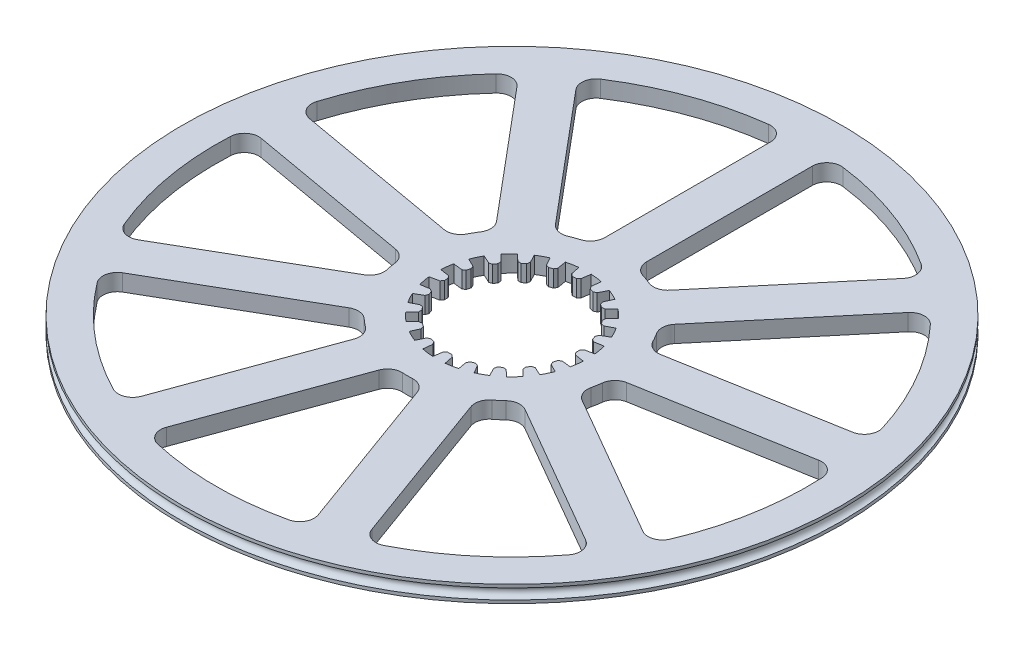
SolidWorks part; units mm, degrees
ref_plane "Front Plane" through (0, 0, 0) normal (0, 0, 1) x (1, 0, 0)
ref_plane "Top Plane" through (0, 0, 0) normal (0, 1, 0) x (1, 0, 0)
ref_plane "Right Plane" through (0, 0, 0) normal (1, 0, 0) x (0, 0, -1)
sketch "Sketch1" plane through (0, 0, 0) normal (0, 1, 0) x (1, 0, 0)
  circle A0 centre (0, 0) radius 2000.25
  dimension "D1" = 4000.5
extrude "Boss-Extrude1" add sketch "Sketch1" along normal blind 101.6
sketch "Sketch2" plane through (0, 101.6, 0) normal (0, 1, 0) x (1, 0, 0)
  circle A0 centre (0, 0) radius 457.2
  dimension "D1" = 914.4
extrude "Cut-Extrude1" cut sketch "Sketch2" against normal through all
sketch "Sketch3" plane through (0, 101.6, 0) normal (0, 1, 0) x (1, 0, 0)
  line L0 (-127, 1695.9045) -> (-127, 690.0124)
  line L1 (127, 690.0124) -> (127, 1695.9045)
  line L2 (992.8188, 1380.7723) -> (346.2438, 610.2142)
  line L3 (540.8191, 446.9462) -> (1187.3941, 1217.5042)
  line L4 (1648.0866, 419.5613) -> (657.4763, 244.89)
  line L5 (701.5829, -5.2512) -> (1692.1932, 169.4201)
  line L6 (1532.1964, -737.967) -> (661.0683, -235.021)
  line L7 (534.0683, -454.9914) -> (1405.1964, -957.9375)
  line L8 (699.3745, -1550.1924) -> (355.3391, -604.963)
  line L9 (116.6572, -691.8361) -> (460.6925, -1637.0655)
  line L10 (-460.6925, -1637.0655) -> (-116.6572, -691.8361)
  line L11 (-355.3391, -604.963) -> (-699.3745, -1550.1924)
  line L12 (-1405.1964, -957.9375) -> (-534.0683, -454.9914)
  line L13 (-661.0683, -235.021) -> (-1532.1964, -737.967)
  line L14 (-1692.1932, 169.4201) -> (-701.5829, -5.2512)
  line L15 (-657.4763, 244.89) -> (-1648.0866, 419.5613)
  line L16 (-1187.3941, 1217.5042) -> (-540.8191, 446.9462)
  line L17 (-346.2438, 610.2142) -> (-992.8188, 1380.7723)
  arc A0 (-629.8844, -80.4399) -> (-619.4098, -139.8443) centre (0, 0) ccw
  arc A1 (-1318.8161, 1220.7017) -> (-1716.5668, 531.7774) centre (0, 0) ccw
  circle A2 centre (0, 0) radius 2000.25 construction
  arc A3 (-225.6198, 1782.8304) -> (-973.1465, 1510.753) centre (0, 0) ccw
  arc A4 (973.1465, 1510.753) -> (225.6198, 1782.8304) centre (0, 0) ccw
  arc A5 (-1794.9237, 87.3931) -> (-1656.7864, -696.0227) centre (0, 0) ccw
  arc A6 (-430.8137, -466.5025) -> (-384.6053, -505.276) centre (0, 0) ccw
  arc A7 (-1431.1665, -1086.8077) -> (-821.7772, -1598.1461) centre (0, 0) ccw
  arc A8 (-397.7506, -1752.4791) -> (397.7506, -1752.4791) centre (0, 0) ccw
  arc A9 (-30.1604, -634.2833) -> (30.1604, -634.2833) centre (0, 0) ccw
  arc A10 (384.6053, -505.276) -> (430.8137, -466.5025) centre (0, 0) ccw
  arc A11 (821.7772, -1598.1461) -> (1431.1665, -1086.8077) centre (0, 0) ccw
  arc A12 (1656.7864, -696.0227) -> (1794.9237, 87.3931) centre (0, 0) ccw
  arc A13 (619.4098, -139.8443) -> (629.8844, -80.4399) centre (0, 0) ccw
  arc A14 (564.3857, 291.022) -> (534.2253, 343.2613) centre (0, 0) ccw
  arc A15 (1716.5668, 531.7774) -> (1318.8161, 1220.7017) centre (0, 0) ccw
  arc A16 (245.2792, 585.7159) -> (188.5962, 606.3468) centre (0, 0) ccw
  arc A17 (-188.5962, 606.3468) -> (-245.2792, 585.7159) centre (0, 0) ccw
  arc A18 (-534.2253, 343.2613) -> (-564.3857, 291.022) centre (0, 0) ccw
  arc A19 (-1648.0866, 419.5613) -> (-1716.5668, 531.7774) centre (-1632.8717, 505.8494) cw
  arc A20 (-1187.3941, 1217.5042) -> (-1318.8161, 1220.7017) centre (-1254.5143, 1161.1836) ccw
  arc A21 (-992.8188, 1380.7723) -> (-973.1465, 1510.753) centre (-925.6985, 1437.0928) cw
  arc A22 (-127, 1695.9045) -> (-225.6198, 1782.8304) centre (-214.6192, 1695.9045) ccw
  arc A23 (127, 1695.9045) -> (225.6198, 1782.8304) centre (214.6192, 1695.9045) cw
  arc A24 (992.8188, 1380.7723) -> (973.1465, 1510.753) centre (925.6985, 1437.0928) ccw
  arc A25 (1187.3941, 1217.5042) -> (1318.8161, 1220.7017) centre (1254.5143, 1161.1836) cw
  arc A26 (1648.0866, 419.5613) -> (1716.5668, 531.7774) centre (1632.8717, 505.8494) ccw
  arc A27 (1692.1932, 169.4201) -> (1794.9237, 87.3931) centre (1707.4082, 83.132) cw
  arc A28 (1532.1964, -737.967) -> (1656.7864, -696.0227) centre (1576.006, -662.0865) ccw
  arc A29 (1405.1964, -957.9375) -> (1431.1665, -1086.8077) centre (1361.3868, -1033.818) cw
  arc A30 (699.3745, -1550.1924) -> (821.7772, -1598.1461) centre (781.7096, -1520.2249) ccw
  arc A31 (460.6925, -1637.0655) -> (397.7506, -1752.4791) centre (378.3574, -1667.0331) cw
  arc A32 (-460.6925, -1637.0655) -> (-397.7506, -1752.4791) centre (-378.3574, -1667.0331) ccw
  arc A33 (-699.3745, -1550.1924) -> (-821.7772, -1598.1461) centre (-781.7096, -1520.2249) cw
  arc A34 (-1405.1964, -957.9375) -> (-1431.1665, -1086.8077) centre (-1361.3868, -1033.818) ccw
  arc A35 (-534.0683, -454.9914) -> (-430.8137, -466.5025) centre (-490.2587, -530.8719) cw
  arc A36 (-355.3391, -604.963) -> (-384.6053, -505.276) centre (-437.6743, -574.9955) ccw
  arc A37 (-116.6572, -691.8361) -> (-30.1604, -634.2833) centre (-34.322, -721.8037) cw
  arc A38 (116.6572, -691.8361) -> (30.1604, -634.2833) centre (34.322, -721.8037) ccw
  arc A39 (355.3391, -604.963) -> (384.6053, -505.276) centre (437.6743, -574.9955) cw
  arc A40 (534.0683, -454.9914) -> (430.8137, -466.5025) centre (490.2587, -530.8719) ccw
  arc A41 (661.0683, -235.021) -> (619.4098, -139.8443) centre (704.8779, -159.1405) cw
  arc A42 (701.5829, -5.2512) -> (629.8844, -80.4399) centre (716.7978, -91.5393) ccw
  arc A43 (657.4763, 244.89) -> (564.3857, 291.022) centre (642.2613, 331.1781) cw
  arc A44 (540.8191, 446.9462) -> (534.2253, 343.2613) centre (607.9393, 390.6256) ccw
  arc A45 (346.2438, 610.2142) -> (245.2792, 585.7159) centre (279.1236, 666.5348) cw
  arc A46 (127, 690.0124) -> (188.5962, 606.3468) centre (214.6192, 690.0124) ccw
  arc A47 (-127, 690.0124) -> (-188.5962, 606.3468) centre (-214.6192, 690.0124) cw
  arc A48 (-346.2438, 610.2142) -> (-245.2792, 585.7159) centre (-279.1236, 666.5348) ccw
  arc A49 (-540.8191, 446.9462) -> (-534.2253, 343.2613) centre (-607.9393, 390.6256) cw
  arc A50 (-657.4763, 244.89) -> (-564.3857, 291.022) centre (-642.2613, 331.1781) ccw
  arc A51 (-701.5829, -5.2512) -> (-629.8844, -80.4399) centre (-716.7978, -91.5393) cw
  arc A52 (-661.0683, -235.021) -> (-619.4098, -139.8443) centre (-704.8779, -159.1405) ccw
  arc A53 (-1532.1964, -737.967) -> (-1656.7864, -696.0227) centre (-1576.006, -662.0865) cw
  arc A54 (-1692.1932, 169.4201) -> (-1794.9237, 87.3931) centre (-1707.4082, 83.132) ccw
  point P44 (0, 0)
  point P49 (-127, 1792.5568)
  point P98 (127, 622.1704)
  point P101 (-127, 622.1704)
  dimension "D1" = 1270
  dimension "D3" = 203.2
  dimension "D5" = 87.6192
  dimension "D2" = 254
  dimension "D4" = 9
extrude "Cut-Extrude2" cut sketch "Sketch3" against normal through all
sketch "Sketch4" plane through (0, 0, 0) normal (0, 0, 1) x (1, 0, 0)
  line L0 (2000.25, 0) -> (2000.25, 101.6) construction
  circle A0 centre (2000.25, 50.8) radius 31.75
  dimension "D1" = 63.5
ref_plane "Plane1" through (0, 50.8, 0) normal (0, 1, 0) x (1, 0, 0)
sketch "Sketch6" plane through (0, 50.8, 0) normal (0, 1, 0) x (1, 0, 0)
  circle A0 centre (0, 0) radius 1714.5
  dimension "D1" = 3429
sweep "Cut-Sweep1" cut profiles "Sketch4" path "Sketch6"
sketch "Sketch7" plane through (0, 101.6, 0) normal (0, 1, 0) x (1, 0, 0)
  line L0 (-48.8401, 454.5839) -> (-37.7961, 400.4709)
  line L1 (24.421, 456.5473) -> (16.2913, 401.9205)
  line L2 (-22.561, 388.3677) -> (1.7264, 389.0186)
  line L3 (-37.7961, 400.4709) -> (-22.561, 388.3677)
  line L4 (16.2913, 401.9205) -> (1.7264, 389.0186)
  line L5 (94.0245, 447.4274) -> (87.8061, 392.5501)
  line L6 (164.3067, 426.6558) -> (139.6942, 377.2148)
  line L7 (139.6942, 377.2148) -> (121.8553, 369.4452)
  line L8 (98.5554, 376.3313) -> (121.8553, 369.4452)
  line L9 (87.8061, 392.5501) -> (98.5554, 376.3313)
  line L10 (227.6852, 396.4736) -> (204.8132, 346.2037)
  line L11 (288.1088, 355.0002) -> (249.4229, 315.5847)
  line L12 (249.4229, 315.5847) -> (230.0561, 313.7079)
  line L13 (210.0246, 327.4571) -> (230.0561, 313.7079)
  line L14 (204.8132, 346.2037) -> (210.0246, 327.4571)
  line L15 (339.0586, 306.7102) -> (301.7718, 265.9685)
  line L16 (383.7089, 248.5947) -> (334.7363, 223.063)
  line L17 (334.7363, 223.063) -> (315.7374, 227.2627)
  line L18 (300.935, 246.529) -> (315.7374, 227.2627)
  line L19 (301.7718, 265.9685) -> (300.935, 246.529)
  line L20 (417.2425, 186.9238) -> (369.1908, 159.6985)
  line L21 (441.7488, 117.8551) -> (387.2834, 108.7063)
  line L22 (387.2834, 108.7063) -> (370.5122, 118.5714)
  line L23 (362.3879, 141.469) -> (370.5122, 118.5714)
  line L24 (369.1908, 159.6985) -> (362.3879, 141.469)
  line L25 (454.5839, 48.8401) -> (400.4709, 37.7961)
  line L26 (456.5473, -24.421) -> (401.9205, -16.2913)
  line L27 (401.9205, -16.2913) -> (389.0186, -1.7264)
  line L28 (388.3677, 22.561) -> (389.0186, -1.7264)
  line L29 (400.4709, 37.7961) -> (388.3677, 22.561)
  line L30 (447.4274, -94.0245) -> (392.5501, -87.8061)
  line L31 (426.6558, -164.3067) -> (377.2148, -139.6942)
  line L32 (377.2148, -139.6942) -> (369.4452, -121.8553)
  line L33 (376.3313, -98.5554) -> (369.4452, -121.8553)
  line L34 (392.5501, -87.8061) -> (376.3313, -98.5554)
  line L35 (396.4736, -227.6852) -> (346.2037, -204.8132)
  line L36 (355.0002, -288.1088) -> (315.5847, -249.4229)
  line L37 (315.5847, -249.4229) -> (313.7079, -230.0561)
  line L38 (327.4571, -210.0246) -> (313.7079, -230.0561)
  line L39 (346.2037, -204.8132) -> (327.4571, -210.0246)
  line L40 (306.7102, -339.0586) -> (265.9685, -301.7718)
  line L41 (248.5947, -383.7089) -> (223.063, -334.7363)
  line L42 (223.063, -334.7363) -> (227.2627, -315.7374)
  line L43 (246.529, -300.935) -> (227.2627, -315.7374)
  line L44 (265.9685, -301.7718) -> (246.529, -300.935)
  line L45 (186.9238, -417.2425) -> (159.6985, -369.1908)
  line L46 (117.8551, -441.7488) -> (108.7063, -387.2834)
  line L47 (108.7063, -387.2834) -> (118.5714, -370.5122)
  line L48 (141.469, -362.3879) -> (118.5714, -370.5122)
  line L49 (159.6985, -369.1908) -> (141.469, -362.3879)
  line L50 (48.8401, -454.5839) -> (37.7961, -400.4709)
  line L51 (-24.421, -456.5473) -> (-16.2913, -401.9205)
  line L52 (-16.2913, -401.9205) -> (-1.7264, -389.0186)
  line L53 (22.561, -388.3677) -> (-1.7264, -389.0186)
  line L54 (37.7961, -400.4709) -> (22.561, -388.3677)
  line L55 (-94.0245, -447.4274) -> (-87.8061, -392.5501)
  line L56 (-164.3067, -426.6558) -> (-139.6942, -377.2148)
  line L57 (-139.6942, -377.2148) -> (-121.8553, -369.4452)
  line L58 (-98.5554, -376.3313) -> (-121.8553, -369.4452)
  line L59 (-87.8061, -392.5501) -> (-98.5554, -376.3313)
  line L60 (-227.6852, -396.4736) -> (-204.8132, -346.2037)
  line L61 (-288.1088, -355.0002) -> (-249.4229, -315.5847)
  line L62 (-249.4229, -315.5847) -> (-230.0561, -313.7079)
  line L63 (-210.0246, -327.4571) -> (-230.0561, -313.7079)
  line L64 (-204.8132, -346.2037) -> (-210.0246, -327.4571)
  line L65 (-339.0586, -306.7102) -> (-301.7718, -265.9685)
  line L66 (-383.7089, -248.5947) -> (-334.7363, -223.063)
  line L67 (-334.7363, -223.063) -> (-315.7374, -227.2627)
  line L68 (-300.935, -246.529) -> (-315.7374, -227.2627)
  line L69 (-301.7718, -265.9685) -> (-300.935, -246.529)
  line L70 (-417.2425, -186.9238) -> (-369.1908, -159.6985)
  line L71 (-441.7488, -117.8551) -> (-387.2834, -108.7063)
  line L72 (-387.2834, -108.7063) -> (-370.5122, -118.5714)
  line L73 (-362.3879, -141.469) -> (-370.5122, -118.5714)
  line L74 (-369.1908, -159.6985) -> (-362.3879, -141.469)
  line L75 (-454.5839, -48.8401) -> (-400.4709, -37.7961)
  line L76 (-456.5473, 24.421) -> (-401.9205, 16.2913)
  line L77 (-401.9205, 16.2913) -> (-389.0186, 1.7264)
  line L78 (-388.3677, -22.561) -> (-389.0186, 1.7264)
  line L79 (-400.4709, -37.7961) -> (-388.3677, -22.561)
  line L80 (-447.4274, 94.0245) -> (-392.5501, 87.8061)
  line L81 (-426.6558, 164.3067) -> (-377.2148, 139.6942)
  line L82 (-377.2148, 139.6942) -> (-369.4452, 121.8553)
  line L83 (-376.3313, 98.5554) -> (-369.4452, 121.8553)
  line L84 (-392.5501, 87.8061) -> (-376.3313, 98.5554)
  line L85 (-396.4736, 227.6852) -> (-346.2037, 204.8132)
  line L86 (-355.0002, 288.1088) -> (-315.5847, 249.4229)
  line L87 (-315.5847, 249.4229) -> (-313.7079, 230.0561)
  line L88 (-327.4571, 210.0246) -> (-313.7079, 230.0561)
  line L89 (-346.2037, 204.8132) -> (-327.4571, 210.0246)
  line L90 (-306.7102, 339.0586) -> (-265.9685, 301.7718)
  line L91 (-248.5947, 383.7089) -> (-223.063, 334.7363)
  line L92 (-223.063, 334.7363) -> (-227.2627, 315.7374)
  line L93 (-246.529, 300.935) -> (-227.2627, 315.7374)
  line L94 (-265.9685, 301.7718) -> (-246.529, 300.935)
  line L95 (-186.9238, 417.2425) -> (-159.6985, 369.1908)
  line L96 (-117.8551, 441.7488) -> (-108.7063, 387.2834)
  line L97 (-108.7063, 387.2834) -> (-118.5714, 370.5122)
  line L98 (-141.469, 362.3879) -> (-118.5714, 370.5122)
  line L99 (-159.6985, 369.1908) -> (-141.469, 362.3879)
  arc A0 (-248.5947, 383.7089) -> (-306.7102, 339.0586) centre (0, 0) ccw
  arc A1 (-355.0002, 288.1088) -> (-396.4736, 227.6852) centre (0, 0) ccw
  arc A2 (-117.8551, 441.7488) -> (-186.9238, 417.2425) centre (0, 0) ccw
  arc A3 (24.421, 456.5473) -> (-48.8401, 454.5839) centre (0, 0) ccw
  arc A4 (164.3067, 426.6558) -> (94.0245, 447.4274) centre (0, 0) ccw
  arc A5 (288.1088, 355.0002) -> (227.6852, 396.4736) centre (0, 0) ccw
  arc A6 (248.5947, -383.7089) -> (306.7102, -339.0586) centre (0, 0) ccw
  arc A7 (355.0002, -288.1088) -> (396.4736, -227.6852) centre (0, 0) ccw
  arc A8 (117.8551, -441.7488) -> (186.9238, -417.2425) centre (0, 0) ccw
  arc A9 (-24.421, -456.5473) -> (48.8401, -454.5839) centre (0, 0) ccw
  arc A10 (-164.3067, -426.6558) -> (-94.0245, -447.4274) centre (0, 0) ccw
  arc A11 (426.6558, -164.3067) -> (447.4274, -94.0245) centre (0, 0) ccw
  arc A12 (456.5473, -24.421) -> (454.5839, 48.8401) centre (0, 0) ccw
  arc A13 (441.7488, 117.8551) -> (417.2425, 186.9238) centre (0, 0) ccw
  arc A14 (383.7089, 248.5947) -> (339.0586, 306.7102) centre (0, 0) ccw
  arc A15 (-426.6558, 164.3067) -> (-447.4274, 94.0245) centre (0, 0) ccw
  arc A16 (-456.5473, 24.421) -> (-454.5839, -48.8401) centre (0, 0) ccw
  arc A17 (-441.7488, -117.8551) -> (-417.2425, -186.9238) centre (0, 0) ccw
  arc A18 (-383.7089, -248.5947) -> (-339.0586, -306.7102) centre (0, 0) ccw
  arc A19 (-288.1088, -355.0002) -> (-227.6852, -396.4736) centre (0, 0) ccw
  point P2 (-35.2564, 388.0274)
  point P7 (14.4219, 389.3588)
  point P128 (0, 0)
  dimension "D1" = 914.4
  dimension "D3" = 100
  dimension "D2" = 100
  dimension "D4" = 20
extrude "Boss-Extrude2" add sketch "Sketch7" against normal up to surface (101.6 mm away) up to face at (1166.5827, 0, 205.7)
sketch "Sketch9" plane through (0, 101.6, 0) normal (0, 1, 0) x (1, 0, 0)
  point P125 (0, 0)
